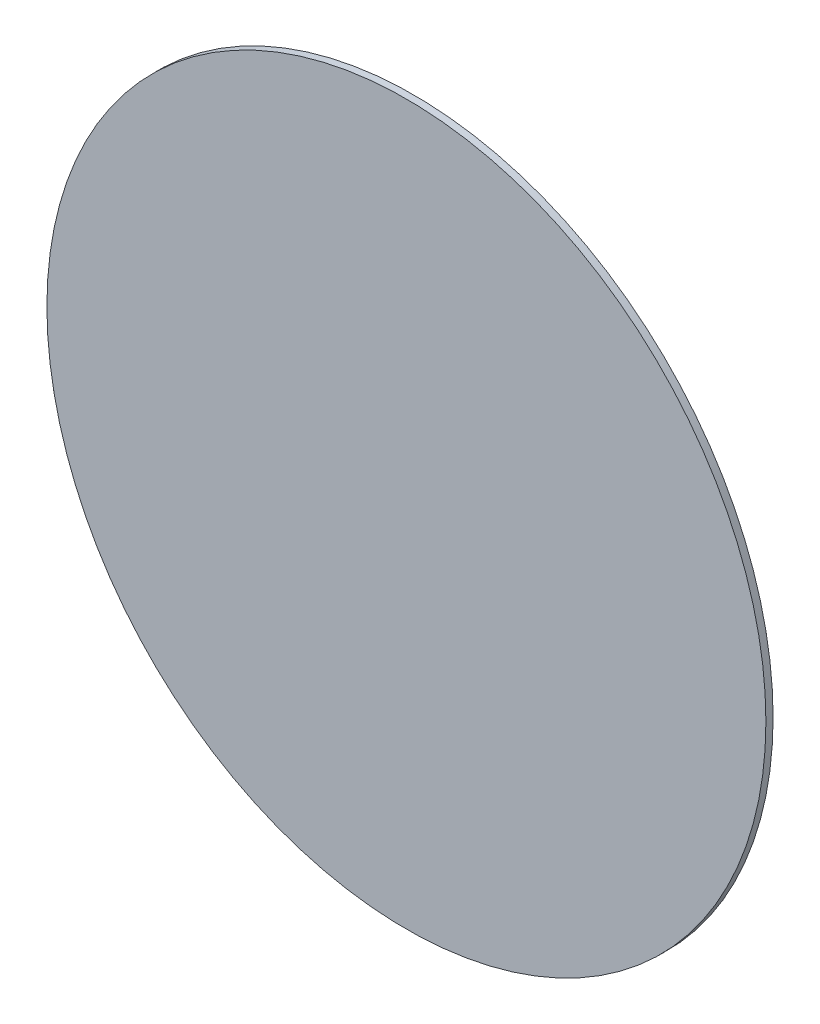
SolidWorks part; units mm, degrees
ref_plane "Ebene vorne" through (0, 0, 0) normal (0, 0, 1) x (1, 0, 0)
ref_plane "Ebene oben" through (0, 0, 0) normal (0, 1, 0) x (1, 0, 0)
ref_plane "Ebene rechts" through (0, 0, 0) normal (1, 0, 0) x (0, 0, -1)
sketch "Skizze1" plane through (0, 0, 0) normal (0, 0, 1) x (1, 0, 0)
  circle A0 centre (0, 0) radius 50
  dimension "D1" = 100
extrude "Aufsatz-Linear austragen1" add sketch "Skizze1" along normal blind 1
